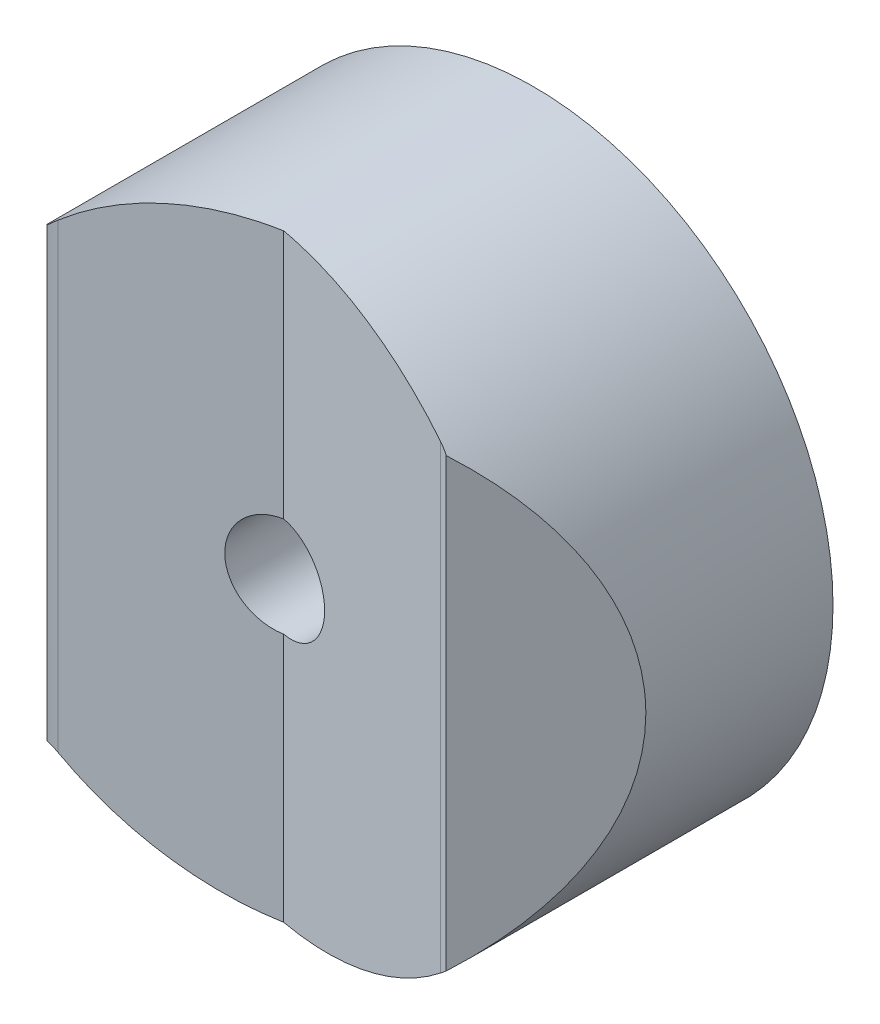
SolidWorks part; units mm, degrees
material "Ceramic Insulation"
ref_plane "Front Plane" through (0, 0, 0) normal (0, 0, 1) x (1, 0, 0)
ref_plane "Top Plane" through (0, 0, 0) normal (0, 1, 0) x (1, 0, 0)
ref_plane "Right Plane" through (0, 0, 0) normal (1, 0, 0) x (0, 0, -1)
sketch "Sketch1" plane through (0, 0, 0) normal (0, 0, 1) x (1, 0, 0)
  circle A0 centre (0, 0) radius 6.35
  circle A1 centre (0, 0) radius 38.1
  dimension "D2" = 12.7
  dimension "D1" = 31.75
extrude "Boss-Extrude1" add sketch "Sketch1" against normal blind 36.5125
sketch "Sketch2" plane through (0, 0, 0) normal (0, 1, 0) x (1, 0, 0)
  line L0 (0, 4.7244) -> (-24.3398, 0.3164)
  line L2 (38.1, 36.5125) -> (-38.1, 36.5125) construction
  line L3 (0, 36.5125) -> (0, 0) construction
  line L4 (-25.4, 0) -> (25.4, 0)
  line L5 (0, 0) -> (0, 4.7244)
  line L6 (38.1, 0) -> (25.4, 0)
  line L7 (-38.1, 12.7) -> (-25.4, 0)
  line L8 (-38.1, 0) -> (38.1, 0) construction
  line L9 (-38.1, 12.7) -> (-38.1, 0)
  line L10 (-38.1, 0) -> (-25.4, 0)
  line L11 (-28.4472, -4.4756) -> (28.4472, -4.4756) construction
  line L12 (0, -4.4756) -> (0, 4.7244) construction
  line L13 (38.1, 12.7) -> (38.1, 0)
  line L14 (38.1, 12.7) -> (25.4, 0)
  line L15 (0, 4.7244) -> (24.3398, 0.3164)
  arc A0 (25.4, 0) -> (28.4472, -4.4756) centre (23.4488, -4.6036) cw construction
  arc A1 (24.3398, 0.3164) -> (25.4, 0) centre (23.4488, -4.6036) cw
  arc A2 (-24.3398, 0.3164) -> (-25.4, 0) centre (-23.4488, -4.6036) ccw
  arc A3 (-25.4, 0) -> (-28.4472, -4.4756) centre (-23.4488, -4.6036) ccw construction
  dimension "D8" = 5
  dimension "D1" = 38.1
  dimension "D2" = 45
  dimension "D4" = 4.7244
  dimension "D6" = 12.7
  dimension "D7" = 9.2
  dimension "D9" = 10.265
extrude "Cut-Extrude2" cut sketch "Sketch2" against normal through all both and the other way through all contours L9 L10 L7 | L0 A2 L4 L5 | A1 L15 L5 L4 | L13 L14 L6
equation "\"ID\"= .5"
equation "\"D2@Sketch1\"=\"ID\""
equation "\"L\"= 1.5"
equation "\"D1@Boss-Extrude1\"=\"L\"-1/16"
equation "\"InsulationThickness\"= 1.25"
equation "\"D1@Sketch1\"=\"InsulationThickness\""
